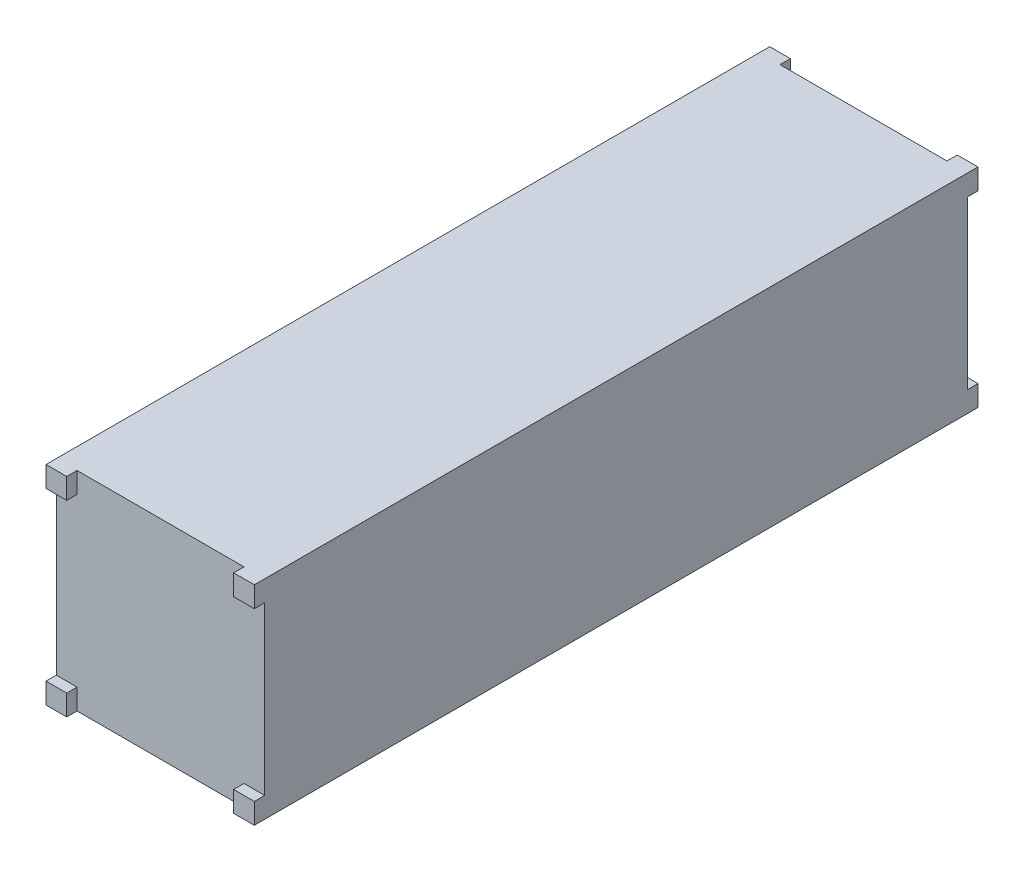
SolidWorks part; units mm, degrees
ref_plane "Front Plane" through (0, 0, 0) normal (0, 0, 1) x (1, 0, 0)
ref_plane "Top Plane" through (0, 0, 0) normal (0, 1, 0) x (1, 0, 0)
ref_plane "Right Plane" through (0, 0, 0) normal (1, 0, 0) x (0, 0, -1)
sketch "Sketch1" plane through (0, 0, 0) normal (0, 0, 1) x (1, 0, 0)
  line L1 (50.3, -50.3) -> (-50.3, -50.3)
  line L2 (50.3, -50.3) -> (50.3, 50.3)
  line L3 (50.3, 50.3) -> (-50.3, 50.3)
  line L4 (-50.3, -50.3) -> (-50.3, 50.3)
  line L5 (50.3, -50.3) -> (-50.3, 50.3) construction
  line L6 (50.3, 50.3) -> (-50.3, -50.3) construction
  point P0 (0, 0)
  dimension "D1" = 100.6
  dimension "D2" = 100.6
extrude "Boss-Extrude1" add sketch "Sketch1" along normal mid plane 339.5
sketch "Sketch2" plane through (0, 0, 169.75) normal (0, 0, 1) x (1, 0, 0)
  line L0 (0, 50.3) -> (0, -50.3) construction
  line L1 (-50.3, 50.3) -> (-40.3, 50.3)
  line L2 (-50.3, 50.3) -> (-50.3, 40.3)
  line L3 (-50.3, 40.3) -> (-40.3, 40.3)
  line L4 (-40.3, 50.3) -> (-40.3, 40.3)
  line L5 (50.3, 50.3) -> (-50.3, 50.3) construction
  line L6 (-50.3, -50.3) -> (50.3, -50.3) construction
  line L7 (50.3, 40.3) -> (40.3, 40.3)
  line L8 (40.3, 50.3) -> (40.3, 40.3)
  line L9 (50.3, 50.3) -> (40.3, 50.3)
  line L10 (50.3, 50.3) -> (50.3, 40.3)
  line L11 (-50.3, 0) -> (50.3, 0) construction
  line L12 (-50.3, 50.3) -> (-50.3, -50.3) construction
  line L13 (50.3, -50.3) -> (50.3, 50.3) construction
  line L14 (50.3, -50.3) -> (50.3, -40.3)
  line L15 (50.3, -50.3) -> (40.3, -50.3)
  line L16 (40.3, -50.3) -> (40.3, -40.3)
  line L17 (50.3, -40.3) -> (40.3, -40.3)
  line L18 (-50.3, -40.3) -> (-40.3, -40.3)
  line L19 (-40.3, -50.3) -> (-40.3, -40.3)
  line L20 (-50.3, -50.3) -> (-40.3, -50.3)
  line L21 (-50.3, -50.3) -> (-50.3, -40.3)
  dimension "D1" = 10
  dimension "D2" = 10
extrude "Boss-Extrude2" add sketch "Sketch2" along normal blind 5
sketch "Sketch3" plane through (0, 0, -169.75) normal (0, 0, -1) x (-1, 0, 0)
  line L0 (0, 50.3) -> (0, 0) construction
  line L1 (-50.3, 50.3) -> (-40.3, 50.3)
  line L2 (-50.3, 50.3) -> (-50.3, 40.3)
  line L3 (-50.3, 40.3) -> (-40.3, 40.3)
  line L4 (-40.3, 50.3) -> (-40.3, 40.3)
  line L5 (-50.3, 50.3) -> (50.3, 50.3) construction
  line L6 (0, 0) -> (50.3, 0) construction
  line L7 (50.3, 50.3) -> (50.3, -50.3) construction
  line L8 (50.3, 40.3) -> (40.3, 40.3)
  line L9 (40.3, 50.3) -> (40.3, 40.3)
  line L10 (50.3, 50.3) -> (40.3, 50.3)
  line L11 (50.3, 50.3) -> (50.3, 40.3)
  line L12 (50.3, -50.3) -> (50.3, -40.3)
  line L13 (50.3, -50.3) -> (40.3, -50.3)
  line L14 (40.3, -50.3) -> (40.3, -40.3)
  line L15 (50.3, -40.3) -> (40.3, -40.3)
  line L16 (-50.3, -40.3) -> (-40.3, -40.3)
  line L17 (-40.3, -50.3) -> (-40.3, -40.3)
  line L18 (-50.3, -50.3) -> (-40.3, -50.3)
  line L19 (-50.3, -50.3) -> (-50.3, -40.3)
  dimension "D1" = 10
  dimension "D2" = 10
extrude "Boss-Extrude3" add sketch "Sketch3" along normal blind 5
